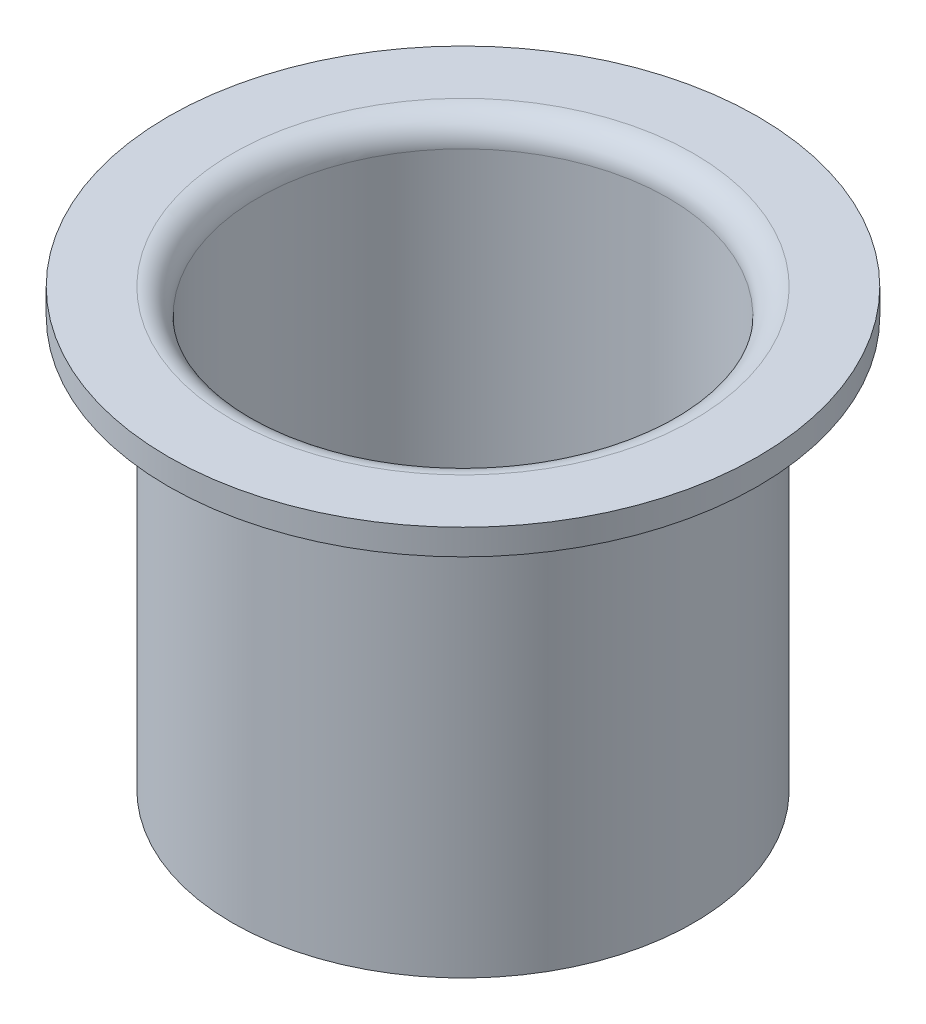
SolidWorks part; units mm, degrees
material "铜"
ref_plane "前视基准面" through (0, 0, 0) normal (0, 0, 1) x (1, 0, 0)
ref_plane "上视基准面" through (0, 0, 0) normal (0, 1, 0) x (1, 0, 0)
ref_plane "右视基准面" through (0, 0, 0) normal (1, 0, 0) x (0, 0, -1)
sketch "草图1" plane through (0, 0, 0) normal (1, 0, 0) x (0, 0, -1)
  line L0 (0, 0) -> (0, 24.6136) construction
  line L1 (8, 0.9065) -> (8, 16.9065)
  line L2 (9, 17.9065) -> (11.5, 17.9065)
  arc A0 (8, 16.9065) -> (9, 17.9065) centre (9, 16.9065) cw
  point P8 (8, 17.9065)
  dimension "D4" = 1
  dimension "D1" = 16
  dimension "D2" = 17
  dimension "D3" = 23
revolve "旋转-薄壁1" add sketch "草图1" angle 360 about L0
